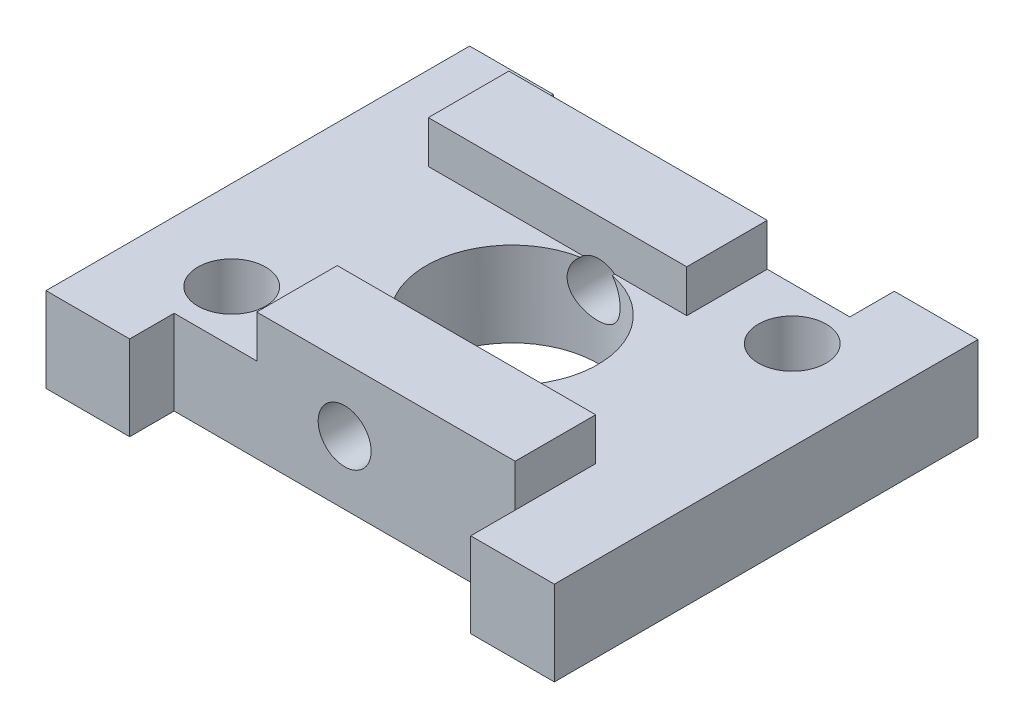
SolidWorks part; units mm, degrees
ref_plane "Front Plane" through (0, 0, 0) normal (0, 0, 1) x (1, 0, 0)
ref_plane "Top Plane" through (0, 0, 0) normal (0, 1, 0) x (1, 0, 0)
ref_plane "Right Plane" through (0, 0, 0) normal (1, 0, 0) x (0, 0, -1)
sketch "Sketch1" plane through (0, 0, 0) normal (0, 1, 0) x (1, 0, 0)
  line L1 (-6, 5) -> (6, 5)
  line L2 (-6, 5) -> (-6, -5)
  line L3 (-6, -5) -> (6, -5)
  line L4 (6, 5) -> (6, -5)
  line L5 (-6, 5) -> (6, -5) construction
  line L6 (-6, -5) -> (6, 5) construction
  circle A0 centre (0, 0) radius 2.025
  point P0 (0, 0)
  dimension "D1" = 4.05
  dimension "D2" = 10
  dimension "D3" = 12
extrude "Boss-Extrude1" add sketch "Sketch1" along normal blind 2
sketch "Sketch2" plane through (0, 2, 0) normal (0, 1, 0) x (1, 0, 0)
  line L0 (6, 5) -> (-6, 5) construction
  line L1 (-4.025, 5) -> (4.025, 5)
  line L2 (-4.025, 5) -> (-4.025, 3.95)
  line L3 (-4.025, 3.95) -> (4.025, 3.95)
  line L4 (4.025, 5) -> (4.025, 3.95)
  line L5 (-6, -5) -> (6, -5) construction
  line L6 (-4.025, -5) -> (4.025, -5)
  line L7 (-4.025, -5) -> (-4.025, -3.95)
  line L8 (-4.025, -3.95) -> (4.025, -3.95)
  line L9 (4.025, -5) -> (4.025, -3.95)
  line L10 (0, -1.1) -> (0, 1.1) construction
  line L11 (-3.891, -2.7245) -> (3.891, 2.7245) construction
  line L15 (-1.1, 0) -> (1.1, 0) construction
  circle A0 centre (3.891, 2.7245) radius 0.8
  circle A1 centre (-3.891, -2.7245) radius 0.8
  point P12 (0, -5)
  point P15 (0, 5)
  point P18 (0, 0)
  point P22 (4.691, 2.7245)
  dimension "D3" = 1.6
  dimension "D1" = 7.9
  dimension "D2" = 8.05
  dimension "D4" = 9.5
  dimension "D5" = 35
extrude "Cut-Extrude1" cut sketch "Sketch2" against normal blind 2
sketch "Sketch3" plane through (0, 2, 0) normal (0, 1, 0) x (1, 0, 0)
  line L1 (-4.025, 3.95) -> (2.075, 3.95)
  line L2 (-4.025, 3.95) -> (-4.025, 2.05)
  line L3 (-4.025, 2.05) -> (2.075, 2.05)
  line L4 (2.075, 3.95) -> (2.075, 2.05)
  line L5 (4.025, -3.95) -> (-2.075, -3.95)
  line L6 (4.025, -3.95) -> (4.025, -2.05)
  line L7 (4.025, -2.05) -> (-2.075, -2.05)
  line L8 (-2.075, -3.95) -> (-2.075, -2.05)
  dimension "D1" = 6.1
  dimension "D2" = 1.9
extrude "Boss-Extrude2" add sketch "Sketch3" along normal blind 1
hole_wizard "M1.6 Tapped Hole1" positions "Sketch4" profile "Sketch5" tap size "M1.6" standard "ISO"
sketch "Sketch4" plane through (0, 0, 3.95) normal (0, 0, 1) x (1, 0, 0)
  line L0 (0, -1.65) -> (0, 1.65) construction
  line L1 (5.5, 0) -> (-5.5, 0) construction
  point P0 (0, 1.5)
  dimension "D1" = 1.5
sketch "Sketch5" plane through (0, 1.5, 3.95) normal (1, 0, 0) x (0, -1, 0)
  line L0 (0, 0) -> (0, 1.925)
  line L1 (0, 1.925) -> (0.625, 1.925)
  line L2 (0.625, 1.925) -> (0.625, 0)
  line L5 (0.625, 0) -> (0, 0)
  line L11 (0, -6.35) -> (0, 107.95) construction
  dimension "Thru Tap Drill Dia." = 1.25
  dimension "Thru Tap Drill Depth" = 1.925
cosmetic thread "Hole Thread1" parameters "D2"=1.6
hole_wizard "M1.6 Tapped Hole2" positions "Sketch6" profile "Sketch7" tap size "M1.6" standard "ISO" end condition up to next
sketch "Sketch6" plane through (0, 0, -3.95) normal (0, 0, -1) x (-1, 0, 0)
  point P0 (0, 1.5)
sketch "Sketch7" plane through (0, 1.5, -3.95) normal (1, 0, 0) x (0, 1, 0)
  line L0 (0, 0) -> (0, 1.925)
  line L1 (0, 1.925) -> (0.625, 1.925)
  line L2 (0.625, 1.925) -> (0.625, 0)
  line L5 (0.625, 0) -> (0, 0)
  line L11 (0, -6.35) -> (0, 107.95) construction
  dimension "Thru Tap Drill Dia." = 1.25
  dimension "Thru Tap Drill Depth" = 1.925
cosmetic thread "Hole Thread2" parameters "D2"=1.6
